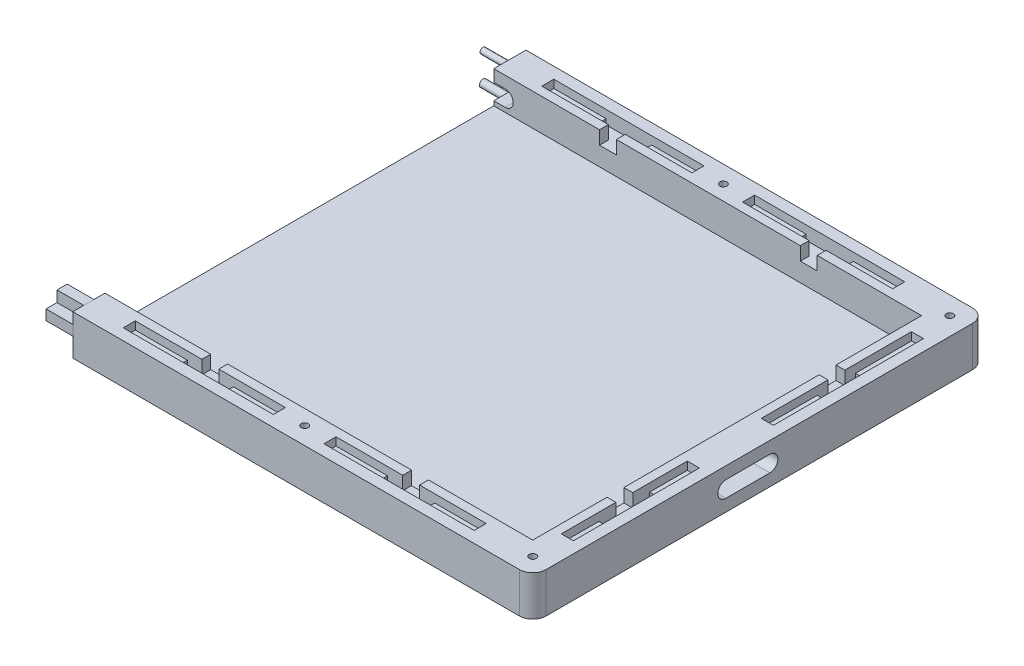
SolidWorks part; units mm, degrees
ref_plane "Front Plane" through (0, 0, 0) normal (0, 0, 1) x (1, 0, 0)
ref_plane "Top Plane" through (0, 0, 0) normal (0, 1, 0) x (1, 0, 0)
ref_plane "Right Plane" through (0, 0, 0) normal (1, 0, 0) x (0, 0, -1)
sketch "Sketch1" plane through (0, 0, 0) normal (0, 1, 0) x (1, 0, 0)
  line L0 (0, 152.7185) -> (0, -149.9342) construction
  line L1 (-90.768, 0) -> (299.0331, 0) construction
  line L2 (0, 72.5) -> (159.54, 72.5)
  line L3 (159.54, 72.5) -> (159.54, -72.5)
  line L4 (159.54, -72.5) -> (0, -72.5)
  line L5 (0, -72.5) -> (0, 72.5)
  dimension "D1" = 159.54
  dimension "D2" = 145
extrude "Boss-Extrude1" add sketch "Sketch1" along normal blind 3
sketch "Sketch3" plane through (0, 0, 0) normal (0, 1, 0) x (1, 0, 0)
  line L0 (0, 105.5814) -> (0, -111.8381) construction
  line L1 (-76.2859, 0) -> (270.0575, 0) construction
  line L2 (0, 72.5) -> (0, 84.5)
  line L3 (0, 84.5) -> (171.54, 84.5)
  line L4 (171.54, 84.5) -> (171.54, -84.5)
  line L5 (171.54, -84.5) -> (0, -84.5)
  line L6 (0, -84.5) -> (0, -72.5)
  line L7 (0, -72.5) -> (159.54, -72.5)
  line L8 (159.54, -72.5) -> (159.54, 72.5)
  line L9 (159.54, 72.5) -> (0, 72.5)
  dimension "D1" = 12
  dimension "D2" = 12
  dimension "D3" = 12
extrude "Boss-Extrude2" add sketch "Sketch3" along normal blind 15
sketch "Sketch4" plane through (0, 15, 0) normal (0, 1, 0) x (1, 0, 0)
  line L0 (45.75, 75.8) -> (45.75, 72.5)
  line L1 (70.6, 75.8) -> (45.75, 75.8)
  line L2 (70.6, 80.3) -> (70.6, 75.8)
  line L3 (14.6, 80.3) -> (70.6, 80.3)
  line L4 (14.6, 75.8) -> (14.6, 80.3)
  line L5 (39.45, 75.8) -> (14.6, 75.8)
  line L6 (39.45, 72.5) -> (39.45, 75.8)
  line L7 (45.75, 72.5) -> (39.45, 72.5)
  line L8 (120.64, 75.8) -> (120.64, 72.5)
  line L9 (145.49, 75.8) -> (120.64, 75.8)
  line L10 (145.49, 80.3) -> (145.49, 75.8)
  line L11 (89.49, 80.3) -> (145.49, 80.3)
  line L12 (89.49, 75.8) -> (89.49, 80.3)
  line L13 (114.34, 75.8) -> (89.49, 75.8)
  line L14 (114.34, 72.5) -> (114.34, 75.8)
  line L15 (120.64, 72.5) -> (114.34, 72.5)
  line L16 (0, 72.5) -> (159.54, 72.5) construction
  line L17 (0, 84.5) -> (0, 72.5) construction
  line L18 (159.54, 72.5) -> (159.54, -72.5) construction
  line L19 (0, 72.5) -> (0, -72.5) construction
  line L20 (145.49, -75.8) -> (120.64, -75.8)
  line L21 (145.49, -80.3) -> (145.49, -75.8)
  line L22 (89.49, -80.3) -> (145.49, -80.3)
  line L23 (89.49, -75.8) -> (89.49, -80.3)
  line L24 (114.34, -75.8) -> (89.49, -75.8)
  line L25 (114.34, -72.5) -> (114.34, -75.8)
  line L26 (120.64, -72.5) -> (114.34, -72.5)
  line L27 (120.64, -75.8) -> (120.64, -72.5)
  line L28 (70.6, -75.8) -> (45.75, -75.8)
  line L29 (70.6, -80.3) -> (70.6, -75.8)
  line L30 (14.6, -80.3) -> (70.6, -80.3)
  line L31 (14.6, -75.8) -> (14.6, -80.3)
  line L32 (39.45, -75.8) -> (14.6, -75.8)
  line L33 (39.45, -72.5) -> (39.45, -75.8)
  line L34 (45.75, -72.5) -> (39.45, -72.5)
  line L35 (45.75, -75.8) -> (45.75, -72.5)
  line L36 (159.54, -72.5) -> (0, -72.5) construction
  line L40 (159.54, -38.5) -> (162.84, -38.5)
  line L49 (159.54, 40.6) -> (162.84, 40.6)
  line L50 (162.84, 40.6) -> (162.84, 65.45)
  line L51 (162.84, 65.45) -> (167.34, 65.45)
  line L52 (167.34, 65.45) -> (167.34, 9.45)
  line L53 (167.34, 9.45) -> (162.84, 9.45)
  line L54 (162.84, 34.3) -> (162.84, 9.45)
  line L55 (159.54, 34.3) -> (162.84, 34.3)
  line L56 (159.54, 40.6) -> (159.54, 34.3)
  line L57 (162.84, -38.5) -> (162.84, -18.15)
  line L58 (162.84, -18.15) -> (167.34, -18.15)
  line L59 (167.34, -18.15) -> (167.34, -65.15)
  line L60 (167.34, -65.15) -> (162.84, -65.15)
  line L61 (162.84, -44.8) -> (162.84, -65.15)
  line L62 (159.54, -44.8) -> (162.84, -44.8)
  line L63 (159.54, -38.5) -> (159.54, -44.8)
  line L64 (0, -72.5) -> (159.54, -72.5) construction
  dimension "D1" = 6.3
  dimension "D2" = 3.3
  dimension "D3" = 4.5
  dimension "D4" = 56
  dimension "D5" = 6.3
  dimension "D6" = 3.3
  dimension "D7" = 4.5
  dimension "D8" = 56
  dimension "D9" = 0
  dimension "D10" = 0
  dimension "D11" = 39.45
  dimension "D12" = 38.9
  dimension "D13" = 56
  dimension "D14" = 39.45
  dimension "D15" = 38.9
  dimension "D16" = 0
  dimension "D17" = 31.9
  dimension "D18" = 6.3
  dimension "D19" = 56
  dimension "D20" = 27.7
  dimension "D21" = 6.3
  dimension "D22" = 47
  dimension "D23" = 56
  dimension "D24" = 3.3
  dimension "D25" = 6.3
  dimension "D26" = 6.3
  dimension "D27" = 3.3
  dimension "D28" = 4.5
  dimension "D29" = 4.5
  dimension "D30" = 3.3
  dimension "D31" = 4.5
  dimension "D32" = 3.3
  dimension "D33" = 4.5
extrude "Cut-Extrude1" cut sketch "Sketch4" against normal blind 3
sketch "Sketch5" plane through (0, 12, 0) normal (0, 1, 0) x (1, 0, 0)
  line L0 (39.45, -75.8) -> (28.5461, -75.8) construction
  line L1 (45.75, -75.8) -> (56.6539, -75.8) construction
  line L2 (39.45, -72.5) -> (39.45, -75.8)
  line L3 (39.45, -75.8) -> (33.9981, -75.8)
  line L4 (33.9981, -75.8) -> (33.9981, -80.3)
  line L5 (33.9981, -80.3) -> (51.2019, -80.3)
  line L6 (51.2019, -80.3) -> (51.2019, -75.8)
  line L7 (45.75, -72.5) -> (39.45, -72.5)
  line L8 (45.75, -72.5) -> (45.75, -75.8)
  line L9 (45.75, -75.8) -> (51.2019, -75.8)
  line L10 (114.34, -75.8) -> (103.0697, -75.8) construction
  line L11 (120.64, -75.8) -> (131.9103, -75.8) construction
  line L12 (114.34, -75.8) -> (108.7049, -75.8)
  line L13 (108.7049, -75.8) -> (108.7049, -80.3)
  line L14 (108.7049, -80.3) -> (126.2751, -80.3)
  line L15 (126.2751, -80.3) -> (126.2751, -75.8)
  line L16 (126.2751, -75.8) -> (120.64, -75.8)
  line L17 (120.64, -75.8) -> (120.64, -72.5)
  line L18 (120.64, -72.5) -> (114.34, -72.5)
  line L19 (114.34, -72.5) -> (114.34, -75.8)
  line L20 (0, -72.5) -> (159.54, -72.5) construction
  line L22 (14.6, -80.3) -> (70.6, -80.3) construction
  line L23 (70.6, -75.8) -> (45.75, -75.8) construction
  line L24 (42.6, -68.4649) -> (42.6, -82.099) construction
  line L26 (89.49, -80.3) -> (145.49, -80.3) construction
  line L27 (114.34, -75.8) -> (89.49, -75.8) construction
  line L28 (117.49, -70.6619) -> (117.49, -81.6393) construction
  line L29 (-14.3619, 0) -> (206.3964, 0) construction
  line L31 (120.64, 72.5) -> (114.34, 72.5)
  line L38 (45.75, 72.5) -> (39.45, 72.5)
  line L48 (159.54, -72.5) -> (159.54, 72.5) construction
  line L49 (159.54, 34.3) -> (162.84, 34.3) construction
  line L56 (162.84, 40.6) -> (159.54, 40.6) construction
  line L59 (157.6179, 36.6875) -> (170.3436, 36.6875) construction
  line L66 (96.0172, 13.3148) -> (96.0172, -25.9889) construction
  line L70 (159.54, -44.8) -> (159.54, -38.5)
  line L75 (159.54, 40.6) -> (162.84, 40.6)
  line L81 (159.54, 34.3) -> (162.84, 34.3)
  line L82 (159.54, 40.6) -> (159.54, 34.3)
  line L94 (158.2993, -40.5875) -> (170.1106, -40.5875) construction
  line L96 (120.64, 72.5) -> (120.64, 75.8)
  line L97 (120.64, 75.8) -> (126.3086, 75.8)
  line L98 (120.64, 75.8) -> (145.49, 75.8) construction
  line L99 (126.3086, 75.8) -> (126.3086, 80.3)
  line L100 (45.75, 72.5) -> (45.75, 75.8)
  line L101 (45.75, 75.8) -> (51.0897, 75.8)
  line L102 (45.75, 75.8) -> (70.6, 75.8) construction
  line L103 (51.0897, 75.8) -> (51.0897, 80.3)
  line L104 (70.6, 80.3) -> (14.6, 80.3) construction
  line L105 (51.0897, 80.3) -> (34.1103, 80.3)
  line L106 (70.6, 80.3) -> (14.6, 80.3) construction
  line L107 (34.1103, 80.3) -> (34.1103, 75.8)
  line L108 (14.6, 75.8) -> (39.45, 75.8) construction
  line L109 (34.1103, 75.8) -> (39.45, 75.8)
  line L110 (39.45, 75.8) -> (39.45, 72.5)
  line L112 (145.49, 80.3) -> (89.49, 80.3) construction
  line L115 (126.3086, 80.3) -> (108.7049, 80.3)
  line L116 (108.7049, 80.3) -> (108.7049, 75.8)
  line L117 (89.49, 75.8) -> (114.34, 75.8) construction
  line L118 (108.7049, 75.8) -> (114.34, 75.8)
  line L119 (114.34, 75.8) -> (114.34, 72.5)
  line L120 (162.84, 40.6) -> (162.84, 44.5797)
  line L121 (162.84, 65.45) -> (162.84, 40.6) construction
  line L122 (162.84, 44.5797) -> (167.34, 44.5797)
  line L123 (167.34, 9.45) -> (167.34, 65.45) construction
  line L124 (167.34, 44.5797) -> (167.34, 30.3203)
  line L125 (167.34, 9.45) -> (167.34, 65.45) construction
  line L126 (167.34, 30.3203) -> (162.84, 30.3203)
  line L127 (162.84, 34.3) -> (162.84, 9.45) construction
  line L128 (162.84, 30.3203) -> (162.84, 34.3)
  line L129 (159.54, -38.5) -> (162.84, -38.5)
  line L130 (162.84, -38.5) -> (162.84, -32.2059)
  line L131 (162.84, -18.15) -> (162.84, -38.5) construction
  line L132 (162.84, -32.2059) -> (167.34, -32.2059)
  line L133 (167.34, -65.15) -> (167.34, -18.15) construction
  line L134 (167.34, -32.2059) -> (167.34, -51.0941)
  line L135 (167.34, -65.15) -> (167.34, -18.15) construction
  line L136 (167.34, -51.0941) -> (162.84, -51.0941)
  line L137 (162.84, -44.8) -> (162.84, -65.15) construction
  line L138 (162.84, -51.0941) -> (162.84, -44.8)
  line L139 (162.84, -44.8) -> (159.54, -44.8)
extrude "Cut-Extrude2" cut sketch "Sketch5" against normal blind 2
sketch "Sketch6" plane through (171.54, 0, 0) normal (1, 0, 0) x (0, 0, -1)
  line L0 (-12.45, 10.5) -> (3.93, 10.5)
  line L1 (-12.45, 4.5) -> (3.93, 4.5)
  line L2 (-15.45, 5.5661) -> (-15.45, 9.4339) construction
  line L5 (-84.5, 7.5) -> (84.5, 7.5) construction
  line L6 (-84.5, 15) -> (-84.5, 0) construction
  line L7 (84.5, 15) -> (84.5, 0) construction
  arc A0 (-12.45, 4.5) -> (-12.45, 10.5) centre (-12.45, 7.5) cw
  arc A1 (3.93, 10.5) -> (3.93, 4.5) centre (3.93, 7.5) cw
  point P6 (-12.45, 10.5)
  point P9 (-15.45, 7.5)
  dimension "D2" = 3
  dimension "D1" = 16.38
  dimension "D3" = 69.05
extrude "Cut-Extrude3" cut sketch "Sketch6" against normal blind 12
sketch "Sketch7" plane through (0, 0, -84.5) normal (0, 0, -1) x (-1, 0, 0)
  line L0 (31.7354, 7.6343) -> (-33.2248, 7.6343) construction
  line L1 (-4.24, 10.6343) -> (12.14, 10.6343)
  line L2 (-4.24, 4.6343) -> (12.14, 4.6343)
  line L3 (-7.24, 4.7002) -> (-7.24, 10.5684) construction
  line L4 (0, 15) -> (0, 0) construction
  line L5 (-171.54, 0) -> (0, 0) construction
  arc A0 (-4.24, 4.6343) -> (-4.24, 10.6343) centre (-4.24, 7.6343) cw
  arc A1 (12.14, 10.6343) -> (12.14, 4.6343) centre (12.14, 7.6343) cw
  point P8 (-4.24, 10.6343)
  point P11 (-7.24, 7.6343)
  dimension "D2" = 3
  dimension "D1" = 16.38
  dimension "D3" = 7.24
  dimension "D4" = 7.6343
extrude "Cut-Extrude4" cut sketch "Sketch7" against normal blind 12
sketch "Sketch8" plane through (0, 0, 0) normal (-1, 0, 0) x (0, 0, 1)
  line L0 (-78.5, 4.6343) -> (-78.5, 0.0234) construction
  line L1 (-72.5, 4.6343) -> (-84.5, 4.6343) construction
  line L2 (-84.5, 12.8171) -> (-72.5, 12.8171) construction
  line L3 (-84.5, 15) -> (-84.5, 10.6343) construction
  line L4 (-72.5, 15) -> (-72.5, 10.6343) construction
  circle A0 centre (-78.5, 12.8171) radius 1.1
  circle A1 centre (-78.5, 2.3288) radius 1.35
  dimension "D1" = 2.2
  dimension "D2" = 2.7
extrude "Boss-Extrude3" add sketch "Sketch8" along normal blind 10
sketch "Sketch9" plane through (0, 0, 0) normal (-1, 0, 0) x (0, 0, 1)
  line L2 (72.5, 9) -> (84.5, 9) construction
  line L3 (72.5, 15) -> (72.5, 3) construction
  line L4 (84.5, 15) -> (84.5, 0) construction
  line L5 (72.5, 3) -> (84.5, 3) construction
  line L6 (78.5, 15) -> (78.5, 3) construction
  line L7 (72.5, 15) -> (84.5, 15) construction
  line L8 (84.4892, 3.011) -> (84.4892, 14.989) construction
  line L9 (84.4892, 14.989) -> (72.5108, 14.989) construction
  line L10 (72.5108, 14.989) -> (72.5117, 3.011) construction
  line L11 (72.5117, 3.011) -> (84.4892, 3.011) construction
  line L12 (84.4892, 3.011) -> (72.5108, 14.989) construction
  line L13 (72.5108, 14.989) -> (84.4892, 14.989) construction
  line L14 (84.4892, 14.989) -> (72.5117, 3.011) construction
  line L15 (78.5, 15.1883) -> (78.5, 3.011) construction
  line L16 (72.5112, 9) -> (83.4994, 9) construction
  line L17 (76.6, 14.989) -> (80.4, 14.989)
  line L18 (84.4892, 7.1) -> (84.4892, 10.9)
  line L19 (80.4, 3.011) -> (76.6, 3.011)
  line L20 (72.5114, 7.1) -> (72.5111, 10.9)
  line L21 (76.6, 14.989) -> (76.6, 10.9)
  line L22 (76.6, 10.9) -> (72.5111, 10.9)
  line L23 (72.5114, 7.1) -> (76.6, 7.1)
  line L24 (76.6, 7.1) -> (76.6, 3.011)
  line L25 (80.4, 3.011) -> (80.4, 7.1)
  line L26 (80.4, 7.1) -> (84.4892, 7.1)
  line L27 (84.4892, 10.9) -> (80.4, 10.9)
  line L28 (80.4, 10.9) -> (80.4, 14.989)
  line L29 (78.5, 9) -> (78.5, 14.989) construction
  line L30 (84.4892, 9) -> (72.5112, 9) construction
  point P26 (78.5, 14.989)
  point P30 (84.4892, 9)
  point P33 (78.5, 3.011)
  point P36 (72.5112, 9)
  point P43 (78.5, 9)
  dimension "D1" = 3.8
  dimension "D2" = 3.8
  dimension "D3" = 3.8
  dimension "D4" = 3.8
  dimension "D5" = 0
extrude "Boss-Extrude5" add sketch "Sketch9" along normal blind 10
fillet "Fillet3" radius 5 1 edges at (171.54, 7.5, 84.5)
fillet "Fillet4" radius 5 1 edges at (171.54, 7.5, -84.5)
sketch "Sketch10" plane through (0, 0, 0) normal (0, -1, 0) x (1, 0, 0)
  circle A0 centre (80.0525, 78.05) radius 1.325
  circle A1 centre (164.8078, 77.7678) radius 1.325
  circle A2 centre (164.8078, -77.7678) radius 1.325
  circle A3 centre (80.0525, -78.05) radius 1.325
  dimension "D1" = 2.65
  dimension "D2" = 2.65
  dimension "D3" = 2.65
  dimension "D4" = 2.65
extrude "Cut-Extrude5" cut sketch "Sketch10" against normal blind 17
sketch "Sketch12" plane through (0, 0, 0) normal (0, -1, 0) x (-1, 0, 0)
  circle A0 centre (-80.0525, -78.05) radius 3
  circle A1 centre (-164.8078, -77.7678) radius 3
  circle A2 centre (-164.8078, 77.7678) radius 3
  circle A3 centre (-80.0525, 78.05) radius 3
  dimension "D1" = 6
  dimension "D2" = 6
  dimension "D3" = 6
  dimension "D4" = 6
extrude "Cut-Extrude6" cut sketch "Sketch12" against normal blind 5
sketch "Sketch13" plane through (0, 0, 0) normal (0, -1, 0) x (1, 0, 0)
  line L0 (80.0525, 78.05) -> (164.8078, 77.7678) construction
  line L1 (122.4301, 77.9089) -> (121.9108, -78.05) construction
  line L2 (80.0525, -64.5) -> (151.54, -64.5) construction
  line L3 (166.54, -84.5) -> (0, -84.5) construction
  line L4 (80.0525, 64.5) -> (151.54, 64.5) construction
  line L5 (0, 84.5) -> (166.54, 84.5) construction
  line L6 (171.54, 79.5) -> (171.54, -79.5) construction
  line L7 (151.54, 64.5) -> (151.54, 84.5) construction
  circle A0 centre (151.54, 64.5) radius 6.25
  circle A1 centre (151.54, -64.5) radius 6.25
  point P18 (151.54, 64.5)
  point P19 (151.54, -64.5)
  dimension "D5" = 12.5
  dimension "D6" = 12.5
  dimension "D1" = 20
  dimension "D2" = 20
  dimension "D3" = 20
  dimension "D4" = 20
extrude "Cut-Extrude7" cut sketch "Sketch13" against normal blind 1
